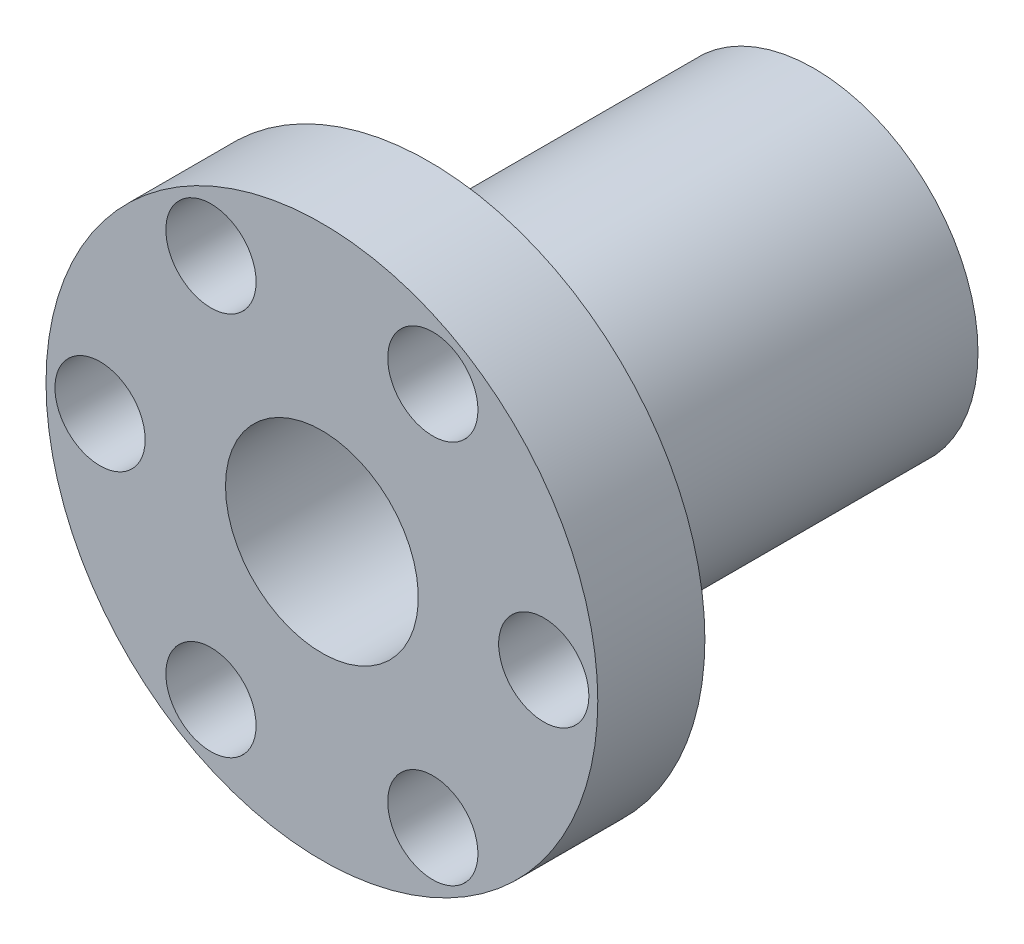
SolidWorks part; units mm, degrees
ref_plane "Plano frontal" through (0, 0, 0) normal (0, 0, 1) x (1, 0, 0)
ref_plane "Plano superior" through (0, 0, 0) normal (0, 1, 0) x (1, 0, 0)
ref_plane "Plano direito" through (0, 0, 0) normal (1, 0, 0) x (0, 0, -1)
sketch "Esboço1" plane through (0, 0, 0) normal (0, 0, 1) x (1, 0, 0)
  circle A0 centre (0, 0) radius 28.62
  dimension "D1" = 57.24
extrude "Ressalto-extrusão1" add sketch "Esboço1" along normal blind 11.11
sketch "Esboço2" plane through (0, 0, 0) normal (0, 0, -1) x (-1, 0, 0)
  circle A1 centre (0, 0) radius 17
  dimension "D1" = 34
extrude "Ressalto-extrusão2" add sketch "Esboço2" along normal blind 39.95
sketch "Esboço3" plane through (0, 0, -39.95) normal (0, 0, -1) x (-1, 0, 0)
  circle A1 centre (0, 0) radius 10
  dimension "D1" = 20
extrude "Corte-extrusão1" cut sketch "Esboço3" against normal through all
sketch "Esboço6" plane through (0, 0, 11.11) normal (0, 0, 1) x (1, 0, 0)
  line L0 (0, 0) -> (28.62, 0) construction
  circle A0 centre (0, 0) radius 28.62 construction
  circle A2 centre (23.015, 0) radius 2.75
  circle A3 centre (0, 0) radius 23.015 construction
  circle A4 centre (11.5075, -19.9316) radius 2.75
  circle A5 centre (-11.5075, -19.9316) radius 2.75
  circle A6 centre (-23.015, 0) radius 2.75
  circle A7 centre (-11.5075, 19.9316) radius 2.75
  circle A8 centre (11.5075, 19.9316) radius 2.75
  dimension "D1" = 5.605
  dimension "D2" = 5.5
  dimension "D3" = 6
extrude "Corte-extrusão3" cut sketch "Esboço6" against normal up to surface (11.11 mm away) up to face at (28.62, 0, 0)
sketch "Esboço4" plane through (0, 0, 0) normal (0, 0, 1) x (1, 0, 0)
  line L0 (0, -28.3531) -> (0, 28.62) construction
  line L1 (-28.62, 0) -> (28.62, 0) construction
  circle A0 centre (0, 0) radius 28.62 construction
  circle A1 centre (-0.1054, 0.0704) radius 23.015 construction
  circle A2 centre (23.015, 0) radius 4.68
  circle A3 centre (11.5075, -19.9316) radius 4.68
  circle A4 centre (-11.5075, -19.9316) radius 4.68
  circle A5 centre (-23.015, 0) radius 4.68
  circle A6 centre (-11.5075, 19.9316) radius 4.68
  circle A7 centre (11.5075, 19.9316) radius 4.68
  dimension "D2" = 6
extrude "Corte-extrusão2" cut sketch "Esboço4" along normal through all from offset 4.39
